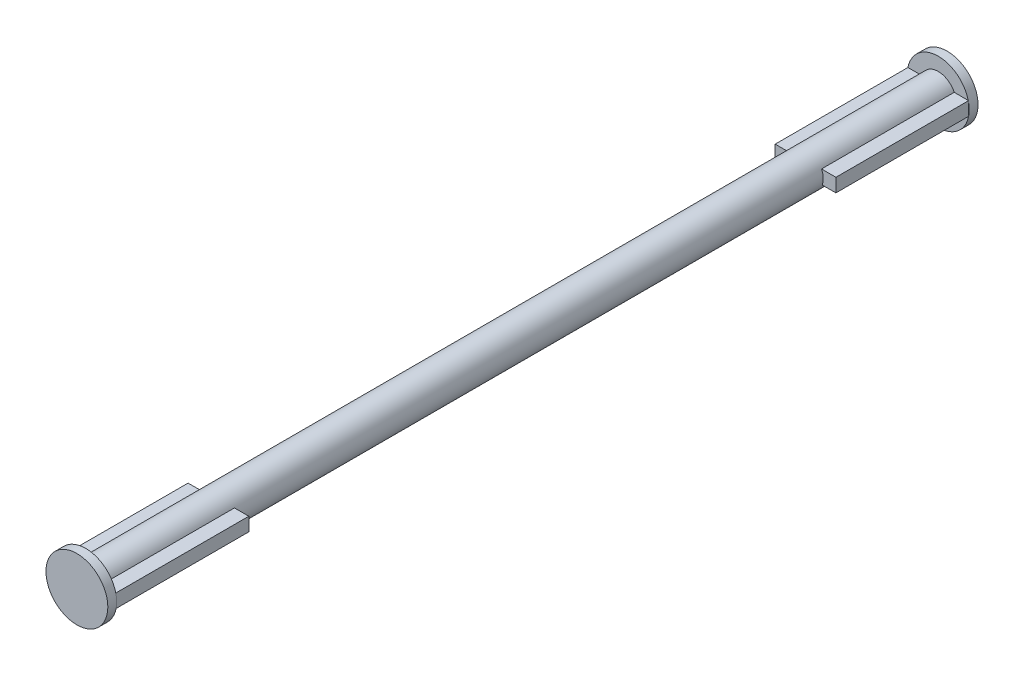
SolidWorks part; units mm, degrees
ref_plane "Front Plane" through (0, 0, 0) normal (0, 0, 1) x (1, 0, 0)
ref_plane "Top Plane" through (0, 0, 0) normal (0, 1, 0) x (1, 0, 0)
ref_plane "Right Plane" through (0, 0, 0) normal (1, 0, 0) x (0, 0, -1)
sketch "Sketch1" plane through (0, 0, 0) normal (0, 0, 1) x (1, 0, 0)
  line L0 (0, -55) -> (0, 55) construction
  circle A0 centre (0, 0) radius 10
  dimension "D1" = 20
extrude "Boss-Extrude2" add sketch "Sketch1" along normal blind 481.8
sketch "Sketch2" plane through (0, 0, 0) normal (0, 0, 1) x (1, 0, 0)
  line L0 (9.03, 4.2965) -> (17.1568, 4.2965)
  line L1 (17.1568, 4.2965) -> (17.1568, -3.362)
  line L2 (17.1568, -3.362) -> (9.4179, -3.362)
  line L3 (-9.03, -4.2965) -> (-17.1568, -4.2965)
  line L4 (-17.1568, -4.2965) -> (-17.1568, 3.362)
  line L5 (-17.1568, 3.362) -> (-9.4179, 3.362)
  circle A0 centre (0, 0) radius 10 construction
  arc A1 (9.03, 4.2965) -> (9.4179, -3.362) centre (0, 0) cw
  arc A2 (-9.03, -4.2965) -> (-9.4179, 3.362) centre (0, 0) cw
  dimension "D1" = 2
extrude "Boss-Extrude4" add sketch "Sketch2" along normal blind 75
sketch "Sketch4" plane through (0, 0, 481.8) normal (0, 0, 1) x (1, 0, 0)
  line L0 (9.03, 4.2965) -> (17.1568, 4.2965)
  line L1 (17.1568, 4.2965) -> (9.03, 4.2965) construction
  line L2 (17.1568, 4.2965) -> (17.1568, -3.362)
  line L3 (17.1568, -3.362) -> (9.4179, -3.362)
  line L4 (-9.03, -4.2965) -> (-17.1568, -4.2965)
  line L5 (-17.1568, -4.2965) -> (-17.1568, 3.362)
  line L6 (-17.1568, 3.362) -> (-9.4179, 3.362)
  circle A0 centre (0, 0) radius 10 construction
  arc A1 (9.4179, -3.362) -> (9.03, 4.2965) centre (0, 0) ccw
  arc A2 (-9.4179, 3.362) -> (-9.03, -4.2965) centre (0, 0) ccw
  dimension "D1" = 2
extrude "Boss-Extrude5" add sketch "Sketch4" against normal blind 75
sketch "Sketch7" plane through (0, 0, 481.8) normal (0, 0, 1) x (1, 0, 0)
  circle A0 centre (0, 0) radius 17.4831
extrude "Boss-Extrude6" add sketch "Sketch7" along normal blind 5
sketch "Sketch8" plane through (0, 0, 0) normal (0, 0, -1) x (-1, 0, 0)
  circle A0 centre (0, 0) radius 17.4831
extrude "Boss-Extrude7" add sketch "Sketch8" along normal blind 5
